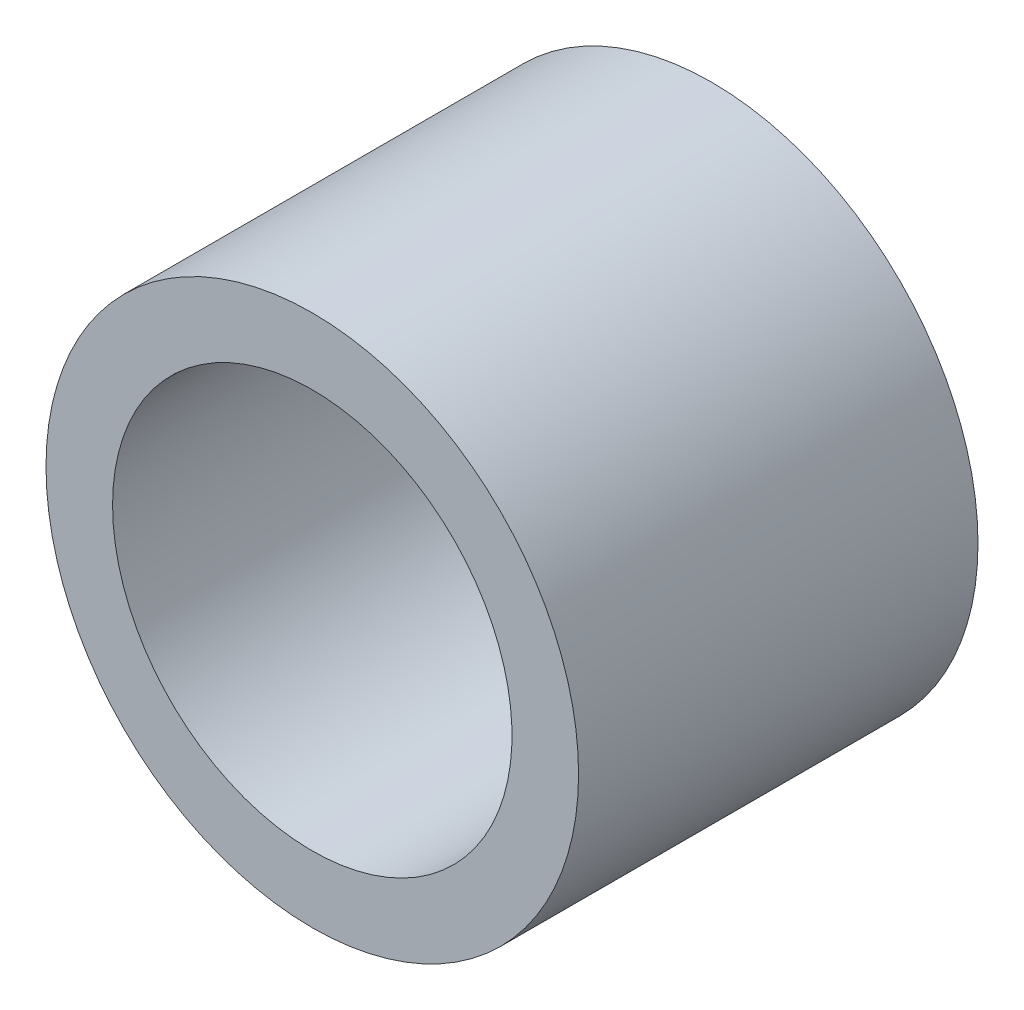
SolidWorks part; units mm, degrees
ref_plane "Front Plane" through (0, 0, 0) normal (0, 0, 1) x (1, 0, 0)
ref_plane "Top Plane" through (0, 0, 0) normal (0, 1, 0) x (1, 0, 0)
ref_plane "Right Plane" through (0, 0, 0) normal (1, 0, 0) x (0, 0, -1)
sketch "Sketch1" plane through (0, 0, 0) normal (0, 0, 1) x (1, 0, 0)
  circle A0 centre (0, 0) radius 12.7
  circle A1 centre (0, 0) radius 9.525
  dimension "D1" = 25.4
  dimension "D2" = 19.05
extrude "Boss-Extrude1" add sketch "Sketch1" along normal mid plane 19.05
